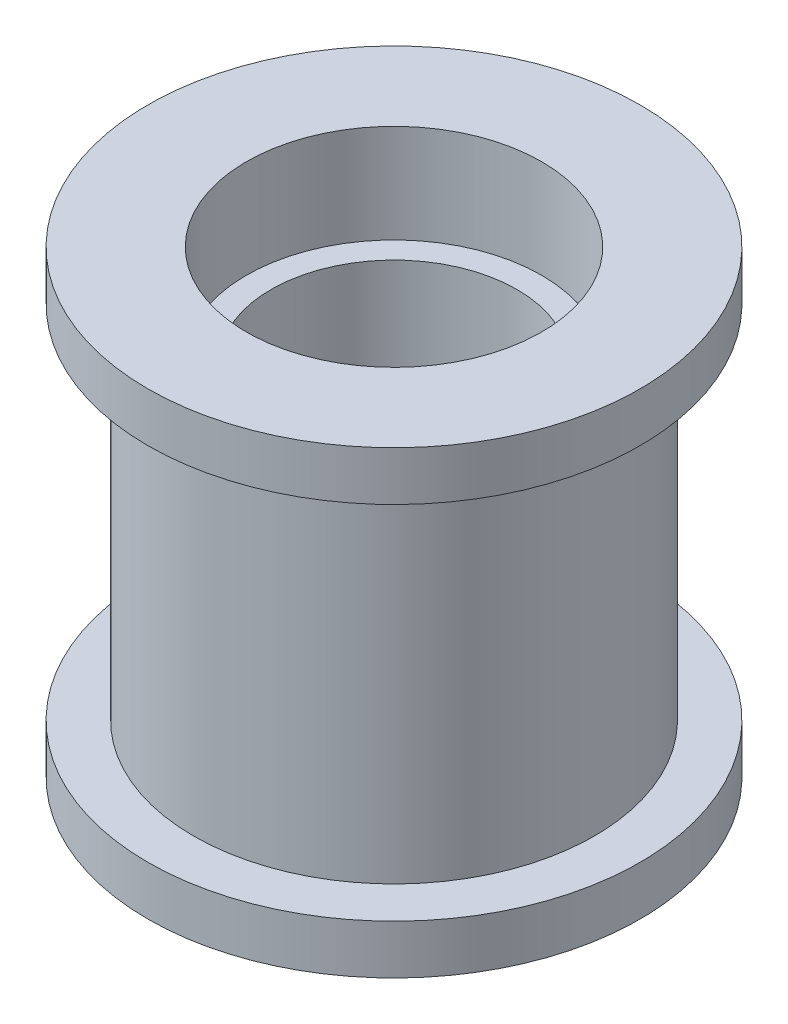
SolidWorks part; units mm, degrees
material "1060 Alloy"
ref_plane "Front Plane" through (0, 0, 0) normal (0, 0, 1) x (1, 0, 0)
ref_plane "Top Plane" through (0, 0, 0) normal (0, 1, 0) x (1, 0, 0)
ref_plane "Right Plane" through (0, 0, 0) normal (1, 0, 0) x (0, 0, -1)
sketch "Sketch1" plane through (0, 0, 0) normal (0, 0, 1) x (1, 0, 0)
  line L0 (0, 0) -> (0, 19.0701) construction
  line L1 (-4.5, 0) -> (-4.5, 3)
  line L2 (-4.5, 3) -> (-3.75, 3)
  line L3 (-3.75, 3) -> (-3.75, 11)
  line L4 (-3.75, 11) -> (-4.5, 11)
  line L5 (-4.5, 11) -> (-4.5, 14)
  line L6 (-4.5, 14) -> (-7.5, 14)
  line L7 (-7.5, 14) -> (-7.5, 12.5)
  line L8 (-7.5, 12.5) -> (-6.11, 12.5)
  line L9 (-6.11, 12.5) -> (-6.11, 1.5)
  line L10 (-6.11, 1.5) -> (-7.5, 1.5)
  line L11 (-7.5, 1.5) -> (-7.5, 0)
  line L12 (-7.5, 0) -> (-4.5, 0)
  line L13 (0, 0) -> (-23.0488, 0) construction
  dimension "D1" = 7.5
  dimension "D2" = 9
  dimension "D3" = 12.22
  dimension "D4" = 15
  dimension "D5" = 1.5
  dimension "D6" = 1.5
  dimension "D7" = 11
  dimension "D8" = 3
  dimension "D9" = 3
revolve "Revolve1" add sketch "Sketch1" angle 360 about L0
